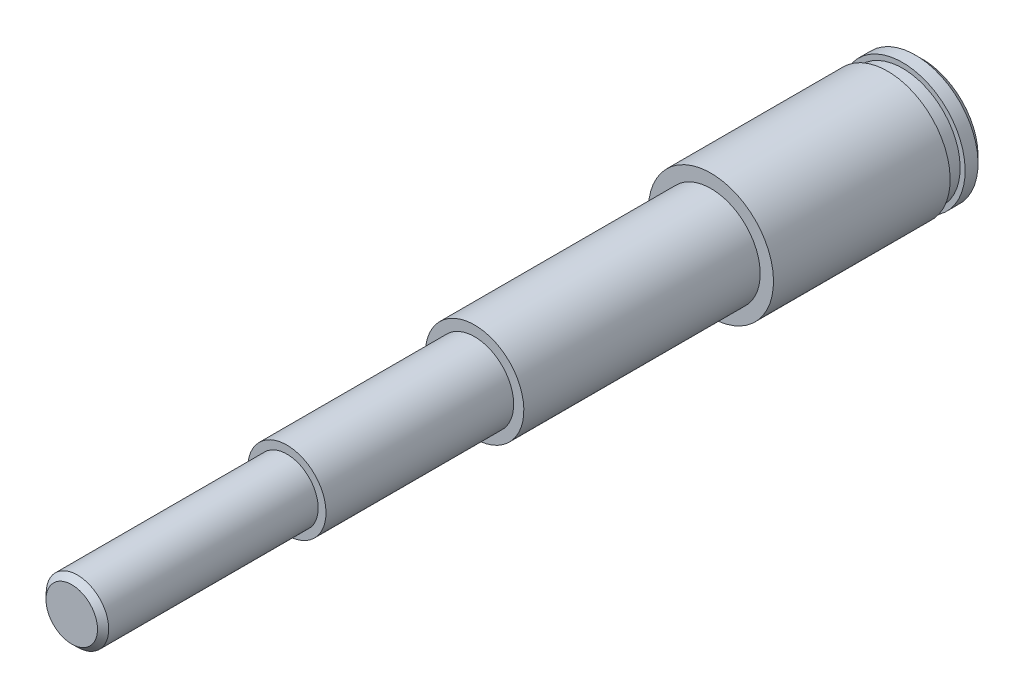
SolidWorks part; units mm, degrees
ref_plane "Front Plane" through (0, 0, 0) normal (0, 0, 1) x (1, 0, 0)
ref_plane "Top Plane" through (0, 0, 0) normal (0, 1, 0) x (1, 0, 0)
ref_plane "Right Plane" through (0, 0, 0) normal (1, 0, 0) x (0, 0, -1)
sketch "Sketch1" plane through (0, 0, 0) normal (1, 0, 0) x (0, 0, -1)
  line L0 (8.1197, 0.3638) -> (-4, 0.3638) construction
  line L1 (-19.8068, 0.3638) -> (-19.8068, 1.6718)
  line L3 (-19.5171, 1.9513) -> (-8.8833, 1.9513)
  line L4 (0, 0.3638) -> (0, 2.2587) construction
  line L5 (-19.8068, 0.3638) -> (23.3793, 0.3638)
  line L7 (0.6455, 2.3482) -> (0.6455, 2.8638)
  line L8 (0.6455, 2.8638) -> (12.6456, 2.8638)
  line L9 (12.6456, 2.8638) -> (12.6456, 3.5388)
  line L10 (12.6456, 3.5388) -> (21.615, 3.5388)
  line L11 (23.0303, 3.5388) -> (23.3793, 3.1898)
  line L12 (23.3793, 3.1898) -> (23.3793, 0.3638)
  line L13 (-8.8833, 1.9513) -> (-8.8833, 2.3482)
  line L14 (-8.8833, 2.3482) -> (0.6455, 2.3482)
  line L15 (-19.5171, 1.9513) -> (-19.8068, 1.6718)
  line L20 (22.377, 3.5388) -> (23.0303, 3.5388)
  line L21 (21.615, 3.5388) -> (21.615, 3.2848)
  line L22 (22.377, 3.5388) -> (22.377, 3.2848)
  line L23 (21.615, 3.2848) -> (22.377, 3.2848)
  point P6 (10.3547, 6.6835)
  point P10 (-19.8068, 1.6718)
  point P26 (-19.5171, 1.9513)
  dimension "D1" = 3.175
  dimension "D2" = 3.9687
  dimension "D3" = 0.254
  dimension "D4" = 0.762
  dimension "D5" = 5
  dimension "D6" = 6.35
revolve "Revolve1" add sketch "Sketch1" angle 360 about L5
